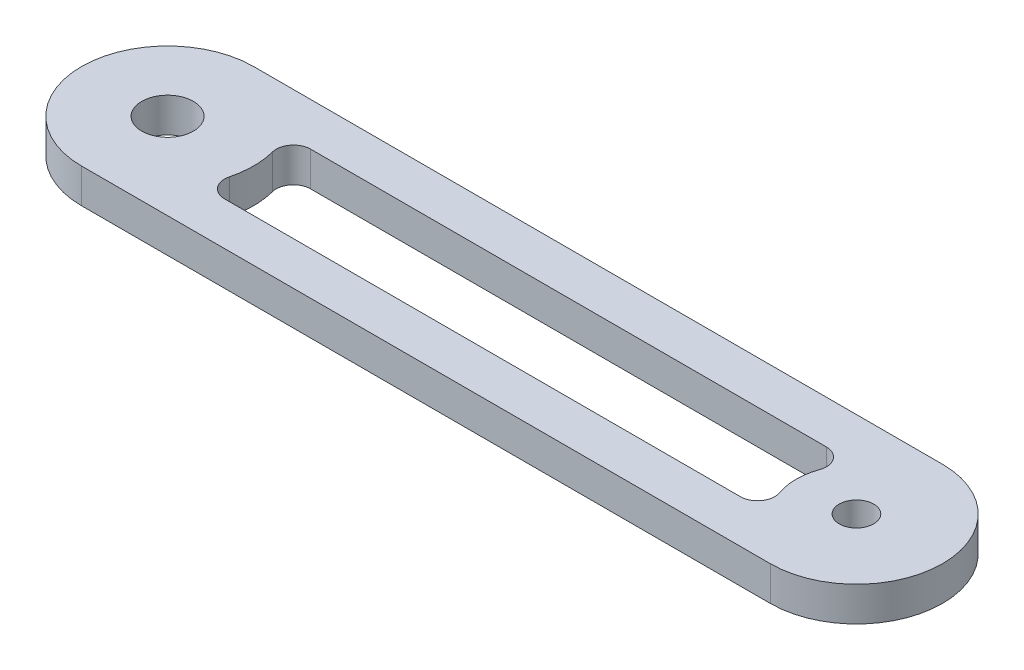
SolidWorks part; units mm, degrees
ref_plane "Front Plane" through (0, 0, 0) normal (0, 0, 1) x (1, 0, 0)
ref_plane "Top Plane" through (0, 0, 0) normal (0, 1, 0) x (1, 0, 0)
ref_plane "Right Plane" through (0, 0, 0) normal (1, 0, 0) x (0, 0, -1)
sketch "Sketch1" plane through (0, 0, 0) normal (0, 1, 0) x (1, 0, 0)
  line L0 (-20, 0) -> (20, 0) construction
  line L1 (-20, 5) -> (20, 5)
  line L2 (-20, -5) -> (20, -5)
  arc A0 (-20, 5) -> (-20, -5) centre (-20, 0) ccw
  arc A1 (20, -5) -> (20, 5) centre (20, 0) ccw
  point P3 (0, 0)
  dimension "D2" = 5
  dimension "D1" = 40
extrude "Boss-Extrude1" add sketch "Sketch1" along normal blind 2 contours L1 A1 L2 A0
sketch "Sketch4" plane through (0, 2, 0) normal (0, 1, 0) x (1, 0, 0)
  line L0 (20, 5) -> (20, -5) construction
  circle A0 centre (20, 0) radius 1
  dimension "D1" = 2
extrude "Cut-Extrude3" cut sketch "Sketch4" against normal blind 12.7
sketch "Sketch5" plane through (0, 2, 0) normal (0, 1, 0) x (1, 0, 0)
  line L0 (-25, 0) -> (-15, 0) construction
  line L1 (-18.6293, 0) -> (-20, 0) construction
  line L3 (-20, 5) -> (20, 5) construction
  line L4 (-20, 5) -> (-20, -5) construction
  line L5 (-20, -5) -> (20, -5) construction
  arc A0 (-20, 5) -> (-20, -5) centre (-20, 0) ccw construction
  circle A1 centre (-20, 0) radius 1.5
  dimension "D1" = 3
extrude "Cut-Extrude4" cut sketch "Sketch5" against normal blind 10 contours A1
sketch "Sketch6" plane through (0, 0, 0) normal (0, -1, 0) x (1, 0, 0)
  line L0 (20, 0) -> (0, 0) construction
  line L1 (15.7574, -2.5) -> (-14.1905, -2.5)
  line L3 (15.7574, 2.5) -> (-14.1905, 2.5)
  line L5 (-20, -5) -> (20, -5) construction
  arc A0 (16.7002, 1.1667) -> (16.7002, -1.1667) centre (20, 0) ccw
  arc A1 (17.5505, -2.5) -> (17.5505, 2.5) centre (20, 0) ccw construction
  arc A4 (16.7002, 1.1667) -> (15.7574, 2.5) centre (15.7574, 1.5) ccw
  arc A5 (15.7574, -2.5) -> (16.7002, -1.1667) centre (15.7574, -1.5) ccw
  arc A6 (-15.1588, -1.25) -> (-15.1588, 1.25) centre (-20, 0) ccw
  arc A8 (-20, 5) -> (-20, -5) centre (-20, 0) ccw construction
  arc A9 (-15.6699, 2.5) -> (-15.6699, -2.5) centre (-20, 0) ccw construction
  arc A10 (-14.1905, 2.5) -> (-15.1588, 1.25) centre (-14.1905, 1.5) ccw
  arc A11 (-14.1905, -2.5) -> (-15.1588, -1.25) centre (-14.1905, -1.5) cw
  point P16 (-15.4174, -2)
  point P23 (-15.4174, 2)
  dimension "D2" = 7
  dimension "D4" = 1
  dimension "D3" = 10
  dimension "D1" = 2.5
extrude "Cut-Extrude5" cut sketch "Sketch6" against normal up to next
equation "\"length\"= 40mm"
equation "\"D1@Sketch1\"=\"length\""
equation "\"radius\"= 5mm"
equation "\"D2@Sketch1\"=\"radius\""
equation "\"small hole radius\"= 2mm"
equation "\"D1@Sketch4\"=\"small hole radius\""
equation "\"large hole radius\"= 10mm"
